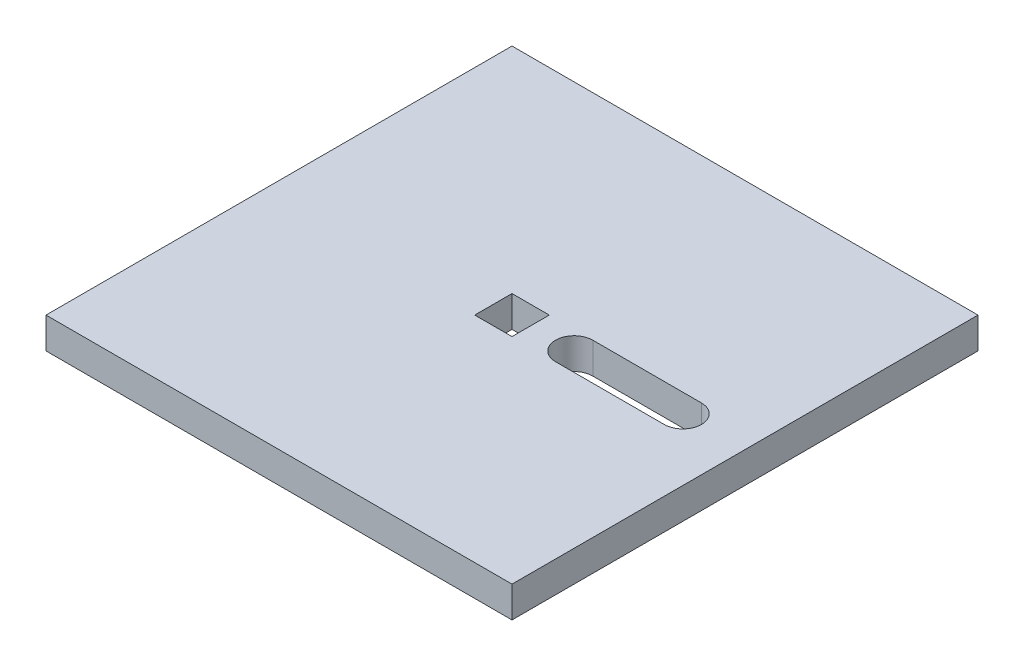
SolidWorks part; units mm, degrees
ref_plane "前基準面" through (0, 0, 0) normal (0, 0, 1) x (1, 0, 0)
ref_plane "上基準面" through (0, 0, 0) normal (0, 1, 0) x (1, 0, 0)
ref_plane "右基準面" through (0, 0, 0) normal (1, 0, 0) x (0, 0, -1)
sketch "Sketch1" plane through (0, 0, 0) normal (0, 1, 0) x (1, 0, 0)
  line L1 (-75, 75) -> (75, 75)
  line L2 (-75, 75) -> (-75, -75)
  line L3 (-75, -75) -> (75, -75)
  line L4 (75, 75) -> (75, -75)
  line L5 (-75, 75) -> (75, -75) construction
  line L6 (-75, -75) -> (75, 75) construction
  point P0 (0, 0)
  dimension "D1" = 150
extrude "Boss-Extrude1" add sketch "Sketch1" along normal blind 10
sketch "Sketch3" plane through (0, 10, 0) normal (0, 1, 0) x (1, 0, 0)
  line L1 (-6, 6) -> (6, 6)
  line L2 (-6, 6) -> (-6, -6)
  line L3 (-6, -6) -> (6, -6)
  line L4 (6, 6) -> (6, -6)
  line L5 (-6, 6) -> (6, -6) construction
  line L6 (-6, -6) -> (6, 6) construction
  point P0 (0, 0)
  dimension "D1" = 12
extrude "Cut-Extrude2" cut sketch "Sketch3" against normal through all
sketch "Sketch2" plane through (0, 10, 0) normal (0, 1, 0) x (1, 0, 0)
  line L0 (0, 0) -> (20, 0) construction
  line L1 (20, 0) -> (55, 0) construction
  line L2 (20, 6) -> (55, 6)
  line L3 (20, -6) -> (55, -6)
  arc A0 (20, 6) -> (20, -6) centre (20, 0) ccw
  arc A1 (55, -6) -> (55, 6) centre (55, 0) ccw
  point P3 (37.5, 0)
  dimension "D2" = 6
  dimension "D1" = 35
  dimension "D3" = 20
extrude "Cut-Extrude1" cut sketch "Sketch2" against normal through all
